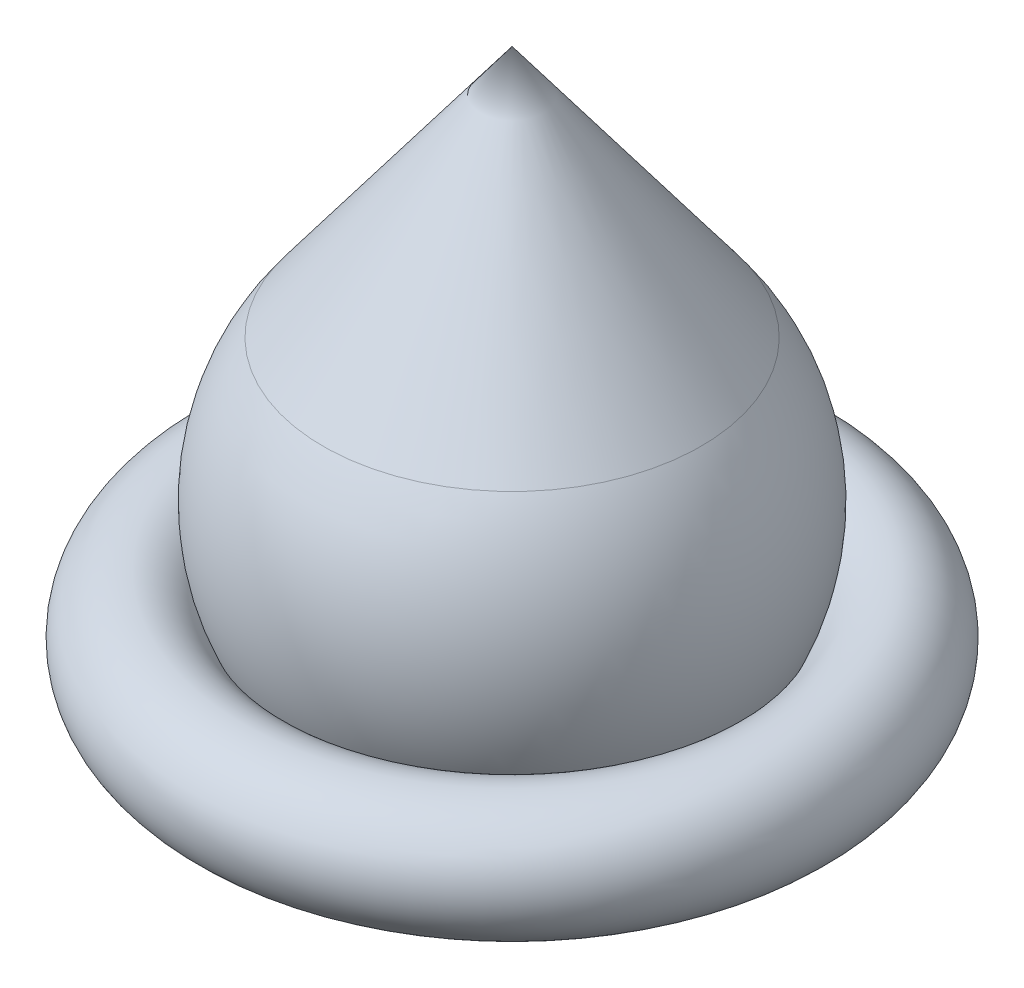
SolidWorks part; units mm, degrees
ref_plane "Front" through (0, 0, 0) normal (0, 0, 1) x (1, 0, 0)
ref_plane "Top" through (0, 0, 0) normal (0, 1, 0) x (1, 0, 0)
ref_plane "Right" through (0, 0, 0) normal (1, 0, 0) x (0, 0, -1)
sketch "Sketch1" plane through (0, 0, 0) normal (0, 0, 1) x (1, 0, 0)
  line L0 (0, 25.4) -> (-7.62, 15.24)
  line L1 (0, 0) -> (0, 25.4)
  line L2 (0, 0) -> (-7.62, 0) construction
  line L3 (-7.62, 0) -> (-7.62, 15.24) construction
  arc A0 (-7.62, 15.24) -> (0, 0) centre (0, 9.525) ccw
  circle A1 centre (-10.9123, 4.7625) radius 2.3813
  dimension "D2" = 4.7625
  dimension "D4" = 9.525
  dimension "D1" = 25.4
  dimension "D3" = 4.7625
revolve "Revolve1" add sketch "Sketch1" angle 360 about L1
